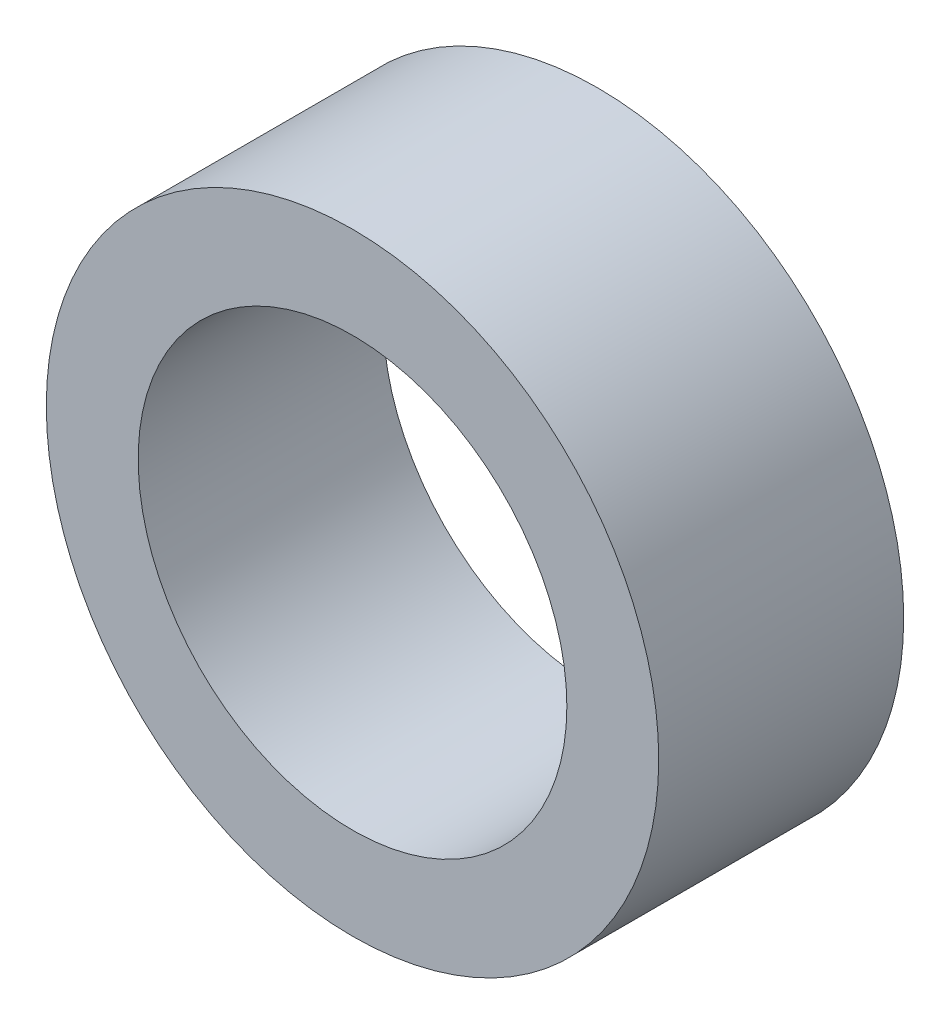
SolidWorks part; units mm, degrees
ref_plane "Front Plane" through (0, 0, 0) normal (0, 0, 1) x (1, 0, 0)
ref_plane "Top Plane" through (0, 0, 0) normal (0, 1, 0) x (1, 0, 0)
ref_plane "Right Plane" through (0, 0, 0) normal (1, 0, 0) x (0, 0, -1)
sketch "Sketch1" plane through (0, 0, 0) normal (0, 0, 1) x (1, 0, 0)
  circle A0 centre (0, 0) radius 35
  circle A1 centre (0, 0) radius 50
  dimension "D1" = 70
  dimension "D2" = 100
extrude "Boss-Extrude1" add sketch "Sketch1" along normal blind 20
mirror "Mirror1" about plane through (0, 0, 0) normal (0, 0, 1) of "Boss-Extrude1"
